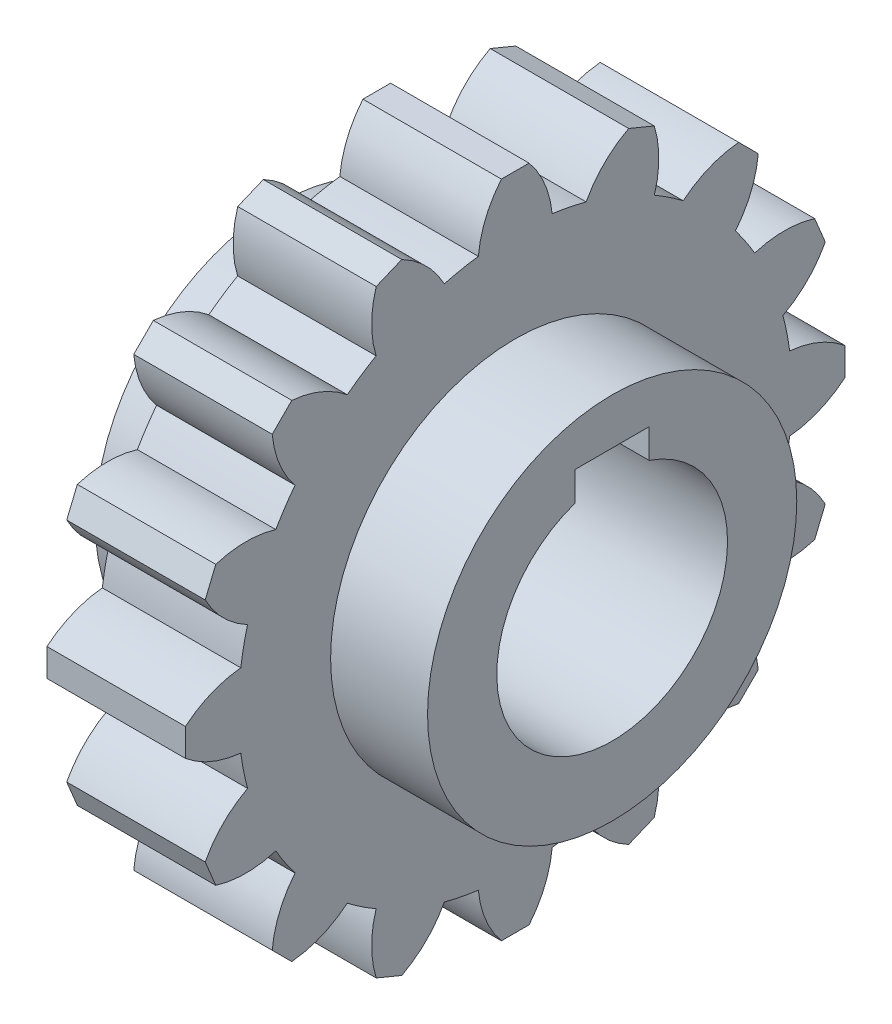
SolidWorks part; units mm, degrees
material "Brass"
ref_plane "Front Plane" through (0, 0, 0) normal (0, 0, 1) x (1, 0, 0)
ref_plane "Top Plane" through (0, 0, 0) normal (0, 1, 0) x (1, 0, 0)
ref_plane "Right Plane" through (0, 0, 0) normal (1, 0, 0) x (0, 0, -1)
sketch "Sketch1" plane through (0, 0, 0) normal (1, 0, 0) x (0, 0, -1)
  circle A0 centre (0, 0) radius 120
  dimension "D1" = 240
extrude "Boss-Extrude1" add sketch "Sketch1" along normal mid plane 60
sketch "Sketch2" plane through (30, 0, 0) normal (1, 0, 0) x (0, 0, -1)
  line L0 (0, 0) -> (0, 36.5674) construction
  line L1 (-6, 142.9285) -> (6, 142.9285)
  arc A0 (-16, 118.9285) -> (16, 118.9285) centre (0, 0) ccw
  circle A1 centre (0, 0) radius 120 construction
  arc A2 (-6, 142.9285) -> (-16, 118.9285) centre (27.8022, 114.761) ccw
  arc A3 (6, 142.9285) -> (16, 118.9285) centre (-27.8022, 114.761) cw
  dimension "D4" = 44
  dimension "D1" = 6
  dimension "D2" = 16
  dimension "D3" = 24
extrude "Boss-Extrude2" add sketch "Sketch2" against normal blind 60
pattern_circular "CirPattern1" count 16 over 360 about axis through (0, 0, 0) along (1, 0, 0) of "Boss-Extrude2"
sketch "Sketch3" plane through (0, 0, 0) normal (1, 0, 0) x (0, 0, -1)
  circle A0 centre (0, 0) radius 80
  dimension "D1" = 160
extrude "Boss-Extrude3" add sketch "Sketch3" along normal mid plane 144
sketch "Sketch4" plane through (72, 0, 0) normal (1, 0, 0) x (0, 0, -1)
  line L0 (0, 0) -> (0, 15.3477) construction
  line L1 (-16, 60) -> (16, 60)
  line L2 (-16, 60) -> (-16, 47.3709)
  line L3 (16, 60) -> (16, 47.3709)
  arc A0 (-16, 47.3709) -> (16, 47.3709) centre (0, 0) ccw
  dimension "D1" = 100
  dimension "D2" = 32
  dimension "D3" = 60
extrude "Cut-Extrude1" cut sketch "Sketch4" against normal through all
